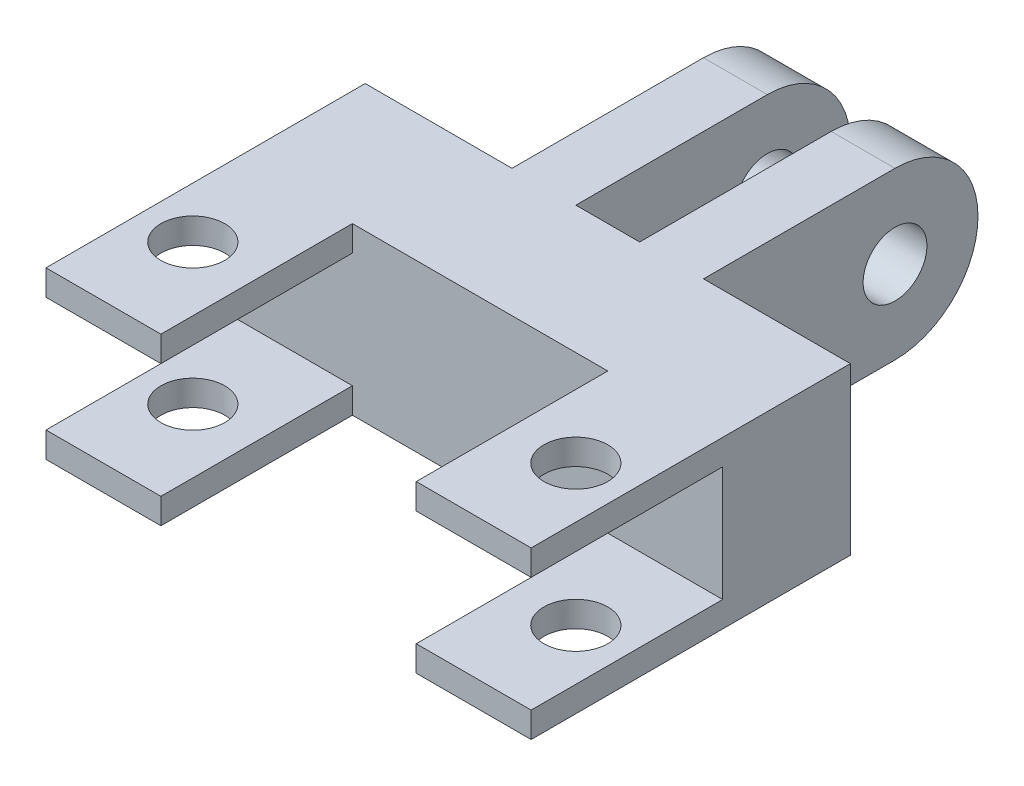
SolidWorks part; units mm, degrees
ref_plane "前视基准面" through (0, 0, 0) normal (0, 0, 1) x (1, 0, 0)
ref_plane "上视基准面" through (0, 0, 0) normal (0, 1, 0) x (1, 0, 0)
ref_plane "右视基准面" through (0, 0, 0) normal (1, 0, 0) x (0, 0, -1)
sketch "草图1" plane through (0, 0, 0) normal (0, 0, 1) x (1, 0, 0)
  line L1 (-19, 6.5) -> (19, 6.5)
  line L2 (-19, 6.5) -> (-19, -6.5)
  line L3 (-19, -6.5) -> (19, -6.5)
  line L4 (19, 6.5) -> (19, -6.5)
  line L5 (0, -6.5) -> (0, 6.5) construction
  line L6 (-19, 0) -> (19, 0) construction
  point P0 (0, 0)
  dimension "D1" = 13
  dimension "D2" = 38
extrude "凸台-拉伸1" add sketch "草图1" along normal blind 25
sketch "草图2" plane through (0, 0, 25) normal (0, 0, 1) x (1, 0, 0)
  line L1 (-25.1368, 4.5) -> (25.1368, 4.5)
  line L2 (-25.1368, 4.5) -> (-25.1368, -4.5)
  line L3 (-25.1368, -4.5) -> (25.1368, -4.5)
  line L4 (25.1368, 4.5) -> (25.1368, -4.5)
  line L5 (0, -4.5) -> (0, 4.5) construction
  line L6 (-25.1368, 0) -> (25.1368, 0) construction
  point P0 (0, 0)
  dimension "D1" = 9
extrude "切除-拉伸1" cut sketch "草图2" against normal blind 15
sketch "草图3" plane through (0, 6.5, 0) normal (0, 1, 0) x (1, 0, 0)
  line L0 (19, -25) -> (-19, -25) construction
  line L1 (-10, -10) -> (10, -10)
  line L2 (-10, -10) -> (-10, -40)
  line L3 (-10, -40) -> (10, -40)
  line L4 (10, -10) -> (10, -40)
  line L5 (0, -40) -> (0, -10) construction
  line L6 (-10, -25) -> (10, -25) construction
  line L7 (19, 0) -> (-19, 0) construction
  point P0 (0, -25)
  dimension "D1" = 10
  dimension "D2" = 20
extrude "切除-拉伸2" cut sketch "草图3" against normal through all
sketch "草图4" plane through (0, 6.5, 0) normal (0, 1, 0) x (1, 0, 0)
  line L0 (0, 0) -> (0, 5.1687) construction
  circle A0 centre (-15, -17.5) radius 2.5
  circle A1 centre (15, -17.5) radius 2.5
  dimension "D2" = 5
  dimension "D1" = 15
extrude "切除-拉伸3" cut sketch "草图4" against normal through all
sketch "草图8" plane through (0, 0, 0) normal (1, 0, 0) x (0, 0, -1)
  line L1 (15, -6.5) -> (0, -6.5)
  line L3 (15, 6.5) -> (0, 6.5)
  line L4 (0, -6.5) -> (0, 6.5)
  line L5 (7.5, 6.5) -> (7.5, -6.5) construction
  line L6 (15, 0) -> (0, 0) construction
  arc A0 (15, 6.5) -> (15, -6.5) centre (15, 0) cw
  circle A1 centre (15, 0) radius 2.5
  point P0 (7.5, 0)
  dimension "D2" = 6.5
  dimension "D3" = 5
  dimension "D1" = 15
extrude "凸台-拉伸3" add sketch "草图8" along normal mid plane 15
sketch "草图9" plane through (0, 6.5, 0) normal (0, 1, 0) x (1, 0, 0)
  line L1 (-2.5, 54.937) -> (2.5, 54.937)
  line L2 (-2.5, 54.937) -> (-2.5, 0)
  line L3 (-2.5, 0) -> (2.5, 0)
  line L4 (2.5, 54.937) -> (2.5, 0)
  line L5 (0, 0) -> (0, 54.937) construction
  line L6 (-2.5, 27.4685) -> (2.5, 27.4685) construction
  point P0 (0, 27.4685)
  dimension "D1" = 5
extrude "切除-拉伸5" cut sketch "草图9" against normal through all
